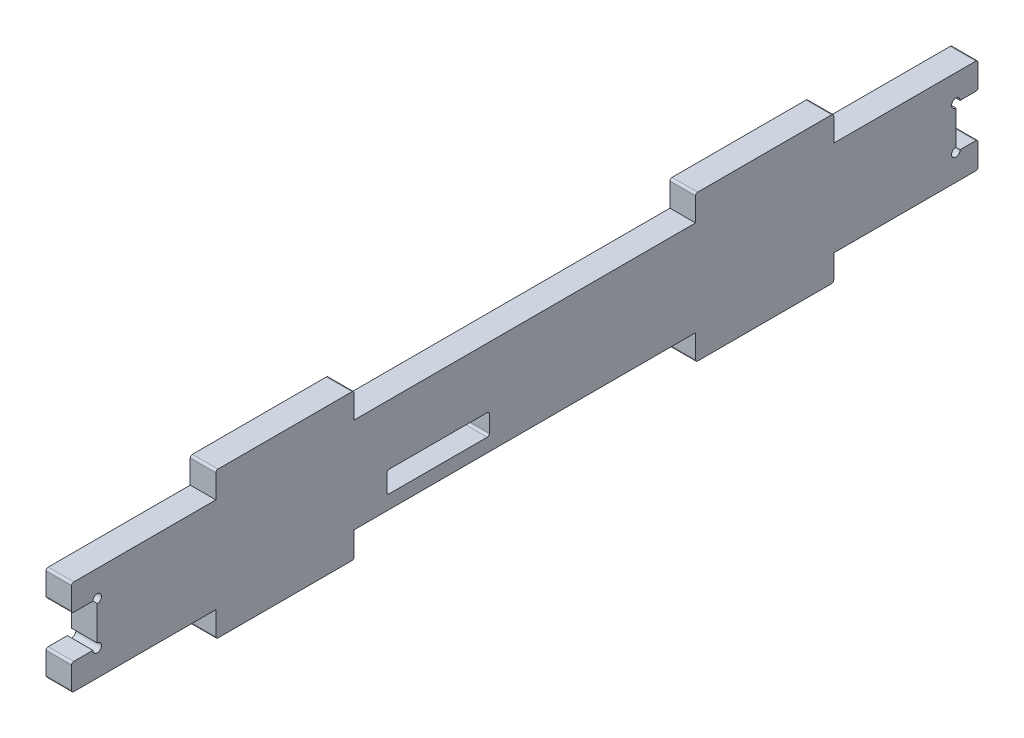
SolidWorks part; units mm, degrees
material "Acrylic (Medium-high impact)"
ref_plane "Front Plane" through (0, 0, 0) normal (0, 0, 1) x (1, 0, 0)
ref_plane "Top Plane" through (0, 0, 0) normal (0, 1, 0) x (1, 0, 0)
ref_plane "Right Plane" through (0, 0, 0) normal (1, 0, 0) x (0, 0, -1)
sketch "Sketch3" plane through (0, 0, 0) normal (1, 0, 0) x (0, 0, -1)
  line L0 (73.2863, 18.7019) -> (88.9863, 18.7019)
  line L1 (17.0863, 1.5644) -> (32.7863, 1.5644)
  line L2 (-0.0637, 4.8144) -> (-0.0637, 7.3832)
  line L3 (17.0863, 18.7019) -> (32.7863, 18.7019)
  line L4 (106.1363, 4.8144) -> (106.1363, 7.3832)
  line L5 (-0.0637, 12.8832) -> (-0.0637, 15.4519)
  line L6 (16.8363, 18.4519) -> (16.8363, 15.7019)
  line L7 (33.0363, 15.7019) -> (73.0363, 15.7019)
  line L8 (33.0363, 18.4519) -> (33.0363, 15.7019)
  line L9 (0.1863, 12.6332) -> (2.4363, 12.6332)
  line L10 (73.0363, 18.4519) -> (73.0363, 15.7019)
  line L11 (89.2363, 15.7019) -> (105.8863, 15.7019)
  line L12 (89.2363, 18.4519) -> (89.2363, 15.7019)
  line L13 (0.1863, 15.7019) -> (16.8363, 15.7019)
  line L14 (106.1363, 12.8832) -> (106.1363, 15.4519)
  line L15 (0.1863, 4.5644) -> (16.8363, 4.5644)
  line L16 (0.1863, 7.6332) -> (2.4363, 7.6332)
  line L17 (73.2863, 1.5644) -> (88.9863, 1.5644)
  line L18 (2.9363, 12.1332) -> (2.9363, 8.1332)
  line L19 (16.8363, 4.5644) -> (16.8363, 1.8144)
  line L20 (105.8863, 12.6332) -> (104.0363, 12.6332)
  line L21 (33.0363, 4.5644) -> (33.0363, 1.8144)
  line L22 (89.2363, 4.5644) -> (105.8863, 4.5644)
  line L23 (73.0363, 4.5644) -> (73.0363, 1.8144)
  line L25 (89.2363, 4.5644) -> (89.2363, 1.8144)
  line L26 (33.0363, 4.5644) -> (73.0363, 4.5644)
  line L27 (105.8863, 7.6332) -> (104.0363, 7.6332)
  line L28 (103.5363, 12.1332) -> (103.5363, 8.1332)
  line L29 (37.1363, 6.1644) -> (48.6363, 6.1644)
  line L30 (36.8863, 6.4144) -> (36.8863, 8.4144)
  line L31 (37.1363, 8.6644) -> (48.6363, 8.6644)
  line L32 (48.8863, 6.4144) -> (48.8863, 8.4144)
  line L33 (36.8863, 6.1644) -> (48.8863, 8.6644) construction
  line L34 (36.8863, 8.6644) -> (48.8863, 6.1644) construction
  arc A0 (2.9363, 12.1332) -> (2.4363, 12.6332) centre (2.9363, 12.6332) ccw
  arc A1 (2.4363, 7.6332) -> (2.9363, 8.1332) centre (2.9363, 7.6332) ccw
  arc A2 (103.5363, 8.1332) -> (104.0363, 7.6332) centre (103.5363, 7.6332) ccw
  arc A3 (104.0363, 12.6332) -> (103.5363, 12.1332) centre (103.5363, 12.6332) ccw
  arc A4 (105.8863, 4.5644) -> (106.1363, 4.8144) centre (105.8863, 4.8144) ccw
  arc A5 (106.1363, 7.3832) -> (105.8863, 7.6332) centre (105.8863, 7.3832) ccw
  arc A6 (105.8863, 12.6332) -> (106.1363, 12.8832) centre (105.8863, 12.8832) ccw
  arc A7 (106.1363, 15.4519) -> (105.8863, 15.7019) centre (105.8863, 15.4519) ccw
  arc A8 (89.2363, 18.4519) -> (88.9863, 18.7019) centre (88.9863, 18.4519) ccw
  arc A9 (73.2863, 18.7019) -> (73.0363, 18.4519) centre (73.2863, 18.4519) ccw
  arc A10 (33.0363, 18.4519) -> (32.7863, 18.7019) centre (32.7863, 18.4519) ccw
  arc A11 (17.0863, 18.7019) -> (16.8363, 18.4519) centre (17.0863, 18.4519) ccw
  arc A12 (0.1863, 15.7019) -> (-0.0637, 15.4519) centre (0.1863, 15.4519) ccw
  arc A13 (-0.0637, 12.8832) -> (0.1863, 12.6332) centre (0.1863, 12.8832) ccw
  arc A14 (0.1863, 7.6332) -> (-0.0637, 7.3832) centre (0.1863, 7.3832) ccw
  arc A15 (-0.0637, 4.8144) -> (0.1863, 4.5644) centre (0.1863, 4.8144) ccw
  arc A16 (16.8363, 1.8144) -> (17.0863, 1.5644) centre (17.0863, 1.8144) ccw
  arc A17 (32.7863, 1.5644) -> (33.0363, 1.8144) centre (32.7863, 1.8144) ccw
  arc A18 (73.0363, 1.8144) -> (73.2863, 1.5644) centre (73.2863, 1.8144) ccw
  arc A19 (88.9863, 1.5644) -> (89.2363, 1.8144) centre (88.9863, 1.8144) ccw
  arc A20 (48.6363, 6.1644) -> (48.8863, 6.4144) centre (48.6363, 6.4144) ccw
  arc A21 (48.6363, 8.6644) -> (48.8863, 8.4144) centre (48.6363, 8.4144) cw
  arc A22 (36.8863, 8.4144) -> (37.1363, 8.6644) centre (37.1363, 8.4144) cw
  arc A23 (37.1363, 6.1644) -> (36.8863, 6.4144) centre (37.1363, 6.4144) cw
  point P24 (42.8863, 7.4144)
  dimension "D19" = 1
  dimension "D25" = 0.5
  dimension "D28" = 0.5
  dimension "D7" = 0.25
  dimension "D33" = 0.5
  dimension "D64" = 0.25
  dimension "D65" = 0.25
  dimension "D66" = 0.25
  dimension "D67" = 0.25
  dimension "D68" = 0.25
  dimension "D69" = 0.25
  dimension "D70" = 0.25
  dimension "D71" = 0.25
  dimension "D72" = 0.25
  dimension "D73" = 0.25
  dimension "D74" = 0.25
  dimension "D75" = 0.25
  dimension "D76" = 0.25
  dimension "D82" = 0.25
  dimension "D3" = 16.9
  dimension "D4" = 106.2
  dimension "D8" = 16.9
  dimension "D9" = 16.9
  dimension "D10" = 3
  dimension "D11" = 17.1375
  dimension "D12" = 5
  dimension "D13" = 3.0688
  dimension "D14" = 3
  dimension "D15" = 16.2
  dimension "D16" = 16.2
  dimension "D17" = 3.0688
  dimension "D18" = 5
  dimension "D20" = 5
  dimension "D21" = 0.5
  dimension "D22" = 0.5
  dimension "D23" = 0.5
  dimension "D24" = 0.5
  dimension "D26" = 0.5
  dimension "D27" = 0.5
  dimension "D29" = 0.25
  dimension "D30" = 0.25
  dimension "D31" = 0.25
  dimension "D32" = 0.25
  dimension "D34" = 0.25
  dimension "D35" = 0.25
  dimension "D36" = 0.25
  dimension "D37" = 0.25
  dimension "D38" = 0.25
  dimension "D39" = 0.25
  dimension "D40" = 0.25
  dimension "D41" = 0.25
  dimension "D42" = 0.25
  dimension "D43" = 0.25
  dimension "D44" = 0.25
  dimension "D45" = 0.25
  dimension "D46" = 0.25
  dimension "D47" = 0.25
  dimension "D48" = 0.25
  dimension "D49" = 0.25
  dimension "D50" = 0.25
  dimension "D51" = 0.25
  dimension "D52" = 0.25
  dimension "D53" = 0.25
  dimension "D54" = 0.25
  dimension "D55" = 0.25
  dimension "D56" = 0.25
  dimension "D57" = 0.25
  dimension "D58" = 0.25
  dimension "D59" = 0.25
  dimension "D60" = 0.25
  dimension "D61" = 0.25
  dimension "D62" = 16.2
  dimension "D63" = 16.2
  dimension "D77" = 16.9
  dimension "D78" = 12
  dimension "D79" = 2.85
  dimension "D80" = 39.95
  dimension "D81" = 2.5
  dimension "D83" = 3
extrude "Boss-Extrude1" add sketch "Sketch3" along normal blind 3
